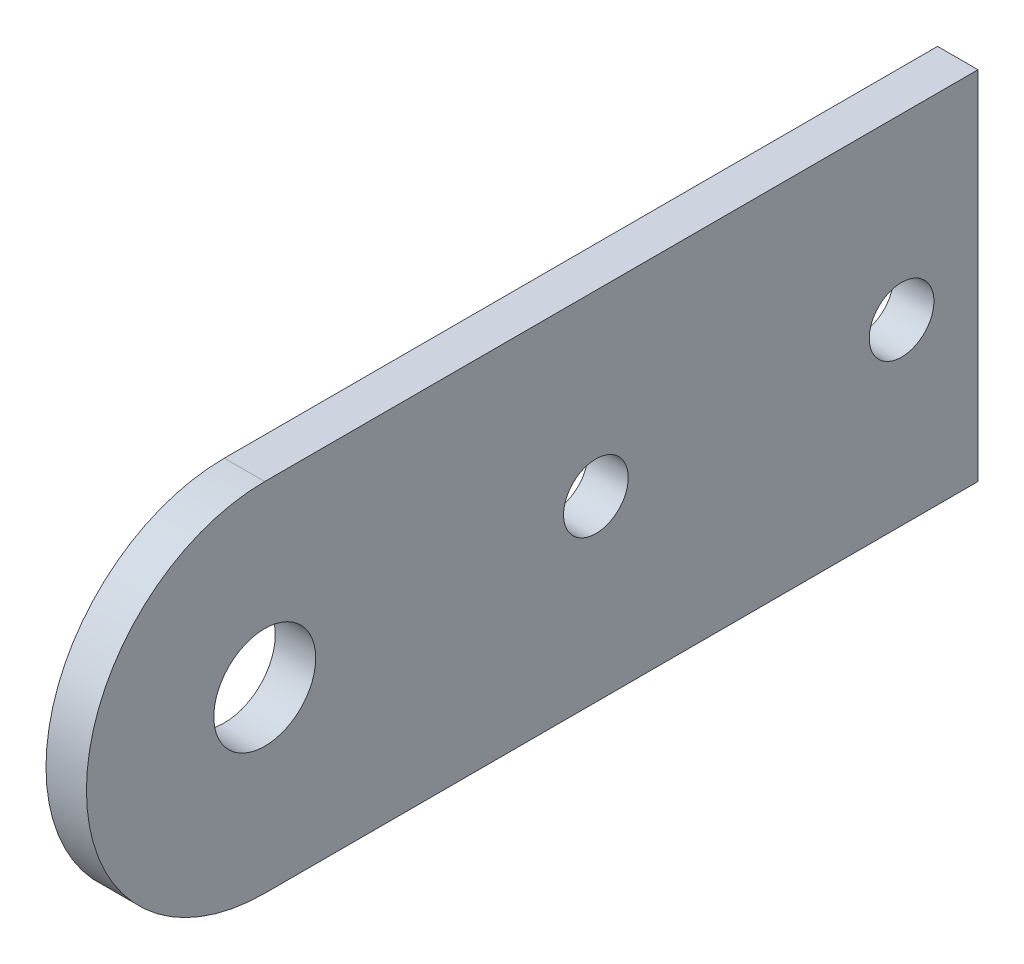
SolidWorks part; units mm, degrees
material "Fundición maleable"
ref_plane "Alzado" through (0, 0, 0) normal (0, 0, 1) x (1, 0, 0)
ref_plane "Planta" through (0, 0, 0) normal (0, 1, 0) x (1, 0, 0)
ref_plane "Vista lateral" through (0, 0, 0) normal (1, 0, 0) x (0, 0, -1)
sketch "Croquis1" plane through (0, 0, 0) normal (1, 0, 0) x (0, 0, -1)
  line L1 (0, 35) -> (140, 35)
  line L2 (0, 35) -> (0, -35)
  line L3 (0, -35) -> (140, -35)
  line L4 (140, 35) -> (140, -35)
  circle A0 centre (0, 0) radius 10
  circle A1 centre (0, 0) radius 35
  circle A2 centre (125, 0) radius 6.35
  circle A3 centre (65, 0) radius 6.35
  dimension "D1" = 20
  dimension "D2" = 70
  dimension "D4" = 12.7
  dimension "D5" = 12.7
  dimension "D7" = 75
  dimension "D3" = 140
  dimension "D6" = 60
  dimension "D8" = 70
extrude "Saliente-Extruir1" add sketch "Croquis1" along normal blind 7.9375 contours L2 A1 A0 | L2 A1 A0 | A1 L3 L4 L1
